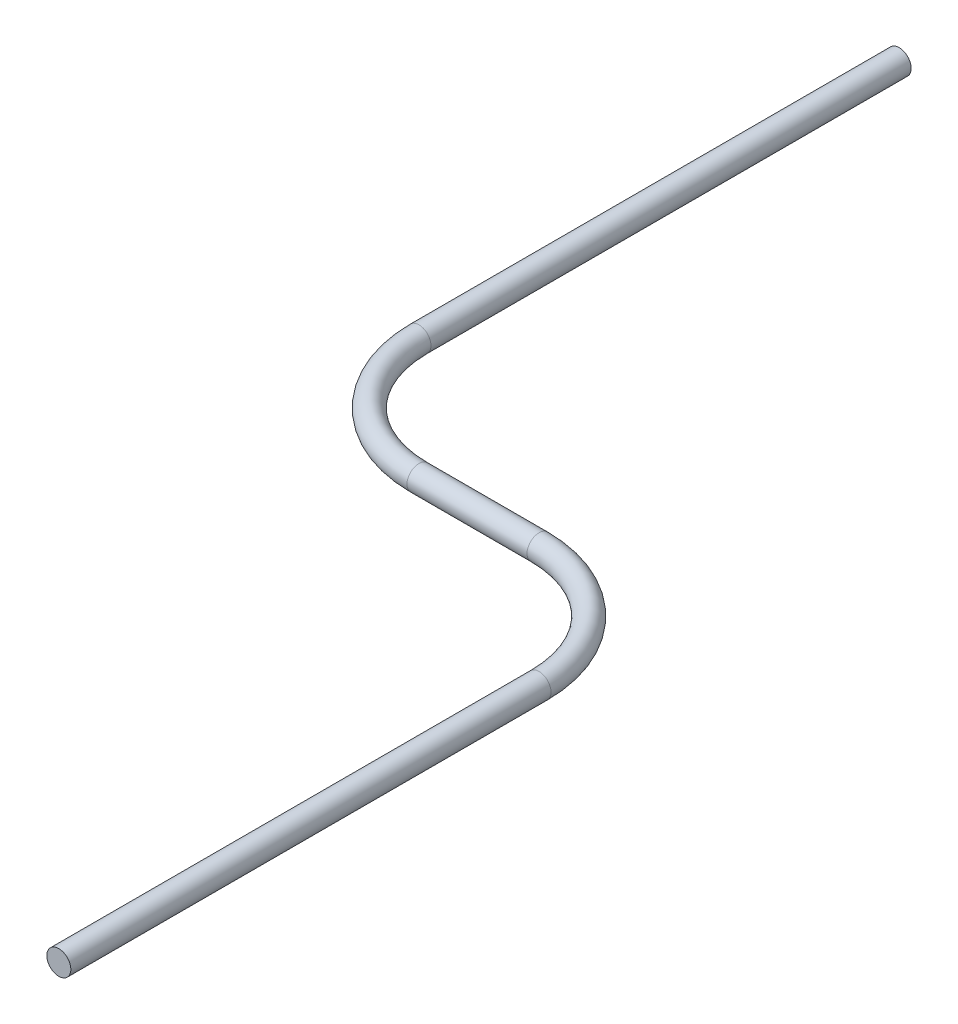
SolidWorks part; units mm, degrees
ref_plane "正面" through (0, 0, 0) normal (0, 0, 1) x (1, 0, 0)
ref_plane "平面" through (0, 0, 0) normal (0, 1, 0) x (1, 0, 0)
ref_plane "右側面" through (0, 0, 0) normal (1, 0, 0) x (0, 0, -1)
sketch "ｽｹｯﾁ1" plane through (0, 0, 0) normal (0, 0, 1) x (1, 0, 0)
  circle A0 centre (0, 0) radius 1
  dimension "D1" = 2
sketch "ｽｹｯﾁ2" plane through (0, 0, 0) normal (0, 1, 0) x (1, 0, 0)
  line L0 (0, 0) -> (0, -40)
  line L1 (10, -50) -> (20, -50)
  line L2 (30, -60) -> (30, -100)
  line L3 (-1, 0) -> (1, 0) construction
  line L4 (-1, 0) -> (1, 0)
  arc A0 (0, -40) -> (10, -50) centre (10, -40) ccw
  arc A1 (20, -50) -> (30, -60) centre (20, -60) cw
  dimension "D1" = 10
  dimension "D2" = 10
  dimension "D3" = 30
  dimension "D4" = 40
  dimension "D5" = 40
sweep "ｽｲｰﾌﾟ1" add profiles "ｽｹｯﾁ1" path "ｽｹｯﾁ2"
